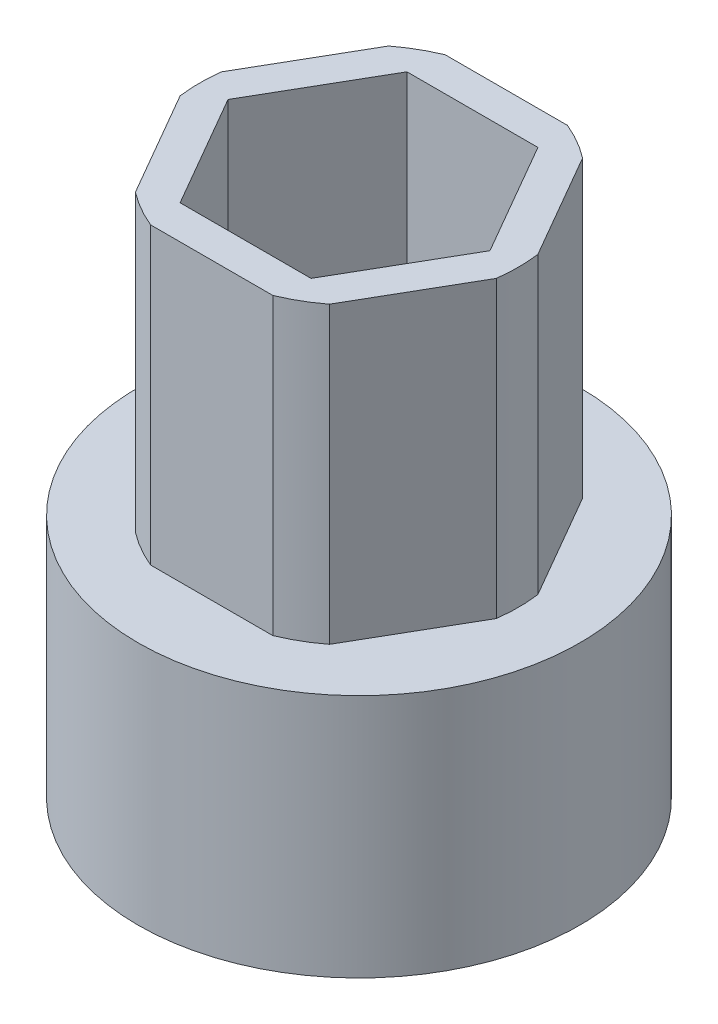
SolidWorks part; units mm, degrees
material "PET"
ref_plane "Front Plane" through (0, 0, 0) normal (0, 0, 1) x (1, 0, 0)
ref_plane "Top Plane" through (0, 0, 0) normal (0, 1, 0) x (1, 0, 0)
ref_plane "Right Plane" through (0, 0, 0) normal (1, 0, 0) x (0, 0, -1)
sketch "Sketch1" plane through (0, 0, 0) normal (0, 1, 0) x (1, 0, 0)
  line L1 (5.6459, 0) -> (2.823, 4.8895)
  line L2 (2.823, 4.8895) -> (-2.823, 4.8895)
  line L3 (-2.823, 4.8895) -> (-5.6459, 0)
  line L4 (-5.6459, 0) -> (-2.823, -4.8895)
  line L5 (-2.823, -4.8895) -> (2.823, -4.8895)
  line L6 (2.823, -4.8895) -> (5.6459, 0)
  circle A0 centre (0, 0) radius 4.8895 construction
  circle A1 centre (0, 0) radius 9.525
  dimension "D1" = 9.779
  dimension "D2" = 19.05
extrude "Boss-Extrude1" add sketch "Sketch1" along normal blind 10.541
sketch "Sketch2" plane through (0, 10.541, 0) normal (0, 1, 0) x (1, 0, 0)
  line L1 (6.8168, 0.893) -> (4.1818, 5.457)
  line L2 (2.635, 6.35) -> (-2.635, 6.35)
  line L3 (-4.1818, 5.457) -> (-6.8168, 0.893)
  line L4 (-6.8168, -0.893) -> (-4.1818, -5.457)
  line L5 (-2.635, -6.35) -> (2.635, -6.35)
  line L6 (4.1818, -5.457) -> (6.8168, -0.893)
  circle A0 centre (0, 0) radius 6.35 construction
  arc A1 (-2.635, 6.35) -> (-4.1818, 5.457) centre (0, 0) ccw
  arc A2 (4.1818, 5.457) -> (2.635, 6.35) centre (0, 0) ccw
  arc A3 (-6.8168, 0.893) -> (-6.8168, -0.893) centre (0, 0) ccw
  arc A4 (-4.1818, -5.457) -> (-2.635, -6.35) centre (0, 0) ccw
  arc A5 (2.635, -6.35) -> (4.1818, -5.457) centre (0, 0) ccw
  arc A6 (6.8168, -0.893) -> (6.8168, 0.893) centre (0, 0) ccw
  line M9 (2.823, 4.8895) -> (5.6459, 0)
  line M10 (5.6459, 0) -> (2.823, -4.8895)
  line M11 (2.823, -4.8895) -> (-2.823, -4.8895)
  line M12 (-2.823, -4.8895) -> (-5.6459, 0)
  line M13 (-5.6459, 0) -> (-2.823, 4.8895)
  line M14 (-2.823, 4.8895) -> (2.823, 4.8895)
  dimension "D1" = 12.7
  dimension "D2" = 13.75
extrude "Boss-Extrude2" add sketch "Sketch2" along normal blind 12.7 contours L6 A6 L1 A2 L2 A1 L3 A3 L4 A4 L5 A5 M14 M9 M10 M11 M12 M13
